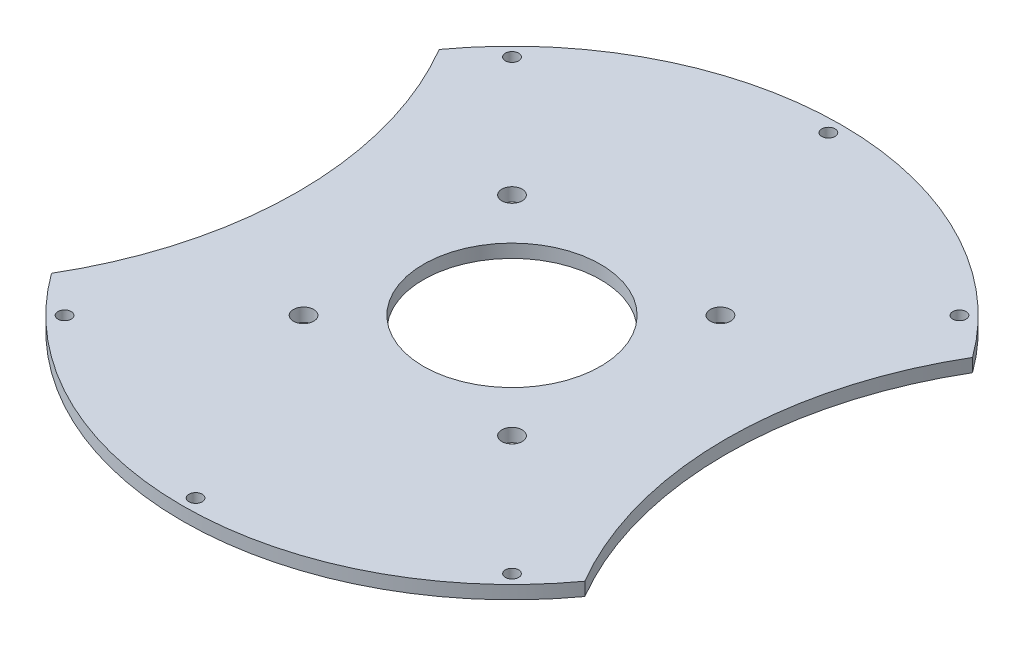
SolidWorks part; units mm, degrees
ref_plane "前视基准面" through (0, 0, 0) normal (0, 0, 1) x (1, 0, 0)
ref_plane "上视基准面" through (0, 0, 0) normal (0, 1, 0) x (1, 0, 0)
ref_plane "右视基准面" through (0, 0, 0) normal (1, 0, 0) x (0, 0, -1)
other "Configuration Table"
sketch "草图2" plane through (0, 0, 0) normal (0, 1, 0) x (1, 0, 0)
  line L1 (0, -103.5765) -> (0, 101.5106) construction
  line L2 (23.55, -23.55) -> (-23.55, -23.55)
  line L3 (23.55, -23.55) -> (23.55, 23.55)
  line L4 (23.55, 23.55) -> (-23.55, 23.55)
  line L5 (-23.55, -23.55) -> (-23.55, 23.55)
  line L6 (23.55, -23.55) -> (-23.55, 23.55) construction
  line L7 (23.55, 23.55) -> (-23.55, -23.55) construction
  arc A0 (60.2604, 43.8057) -> (-60.2604, 43.8057) centre (0, 0) ccw
  circle A2 centre (0, 71.5) radius 1.5
  circle A3 centre (50.5581, 50.5581) radius 1.5
  circle A5 centre (50.5581, -50.5581) radius 1.5
  circle A6 centre (0, -71.5) radius 1.5
  circle A7 centre (-50.5581, -50.5581) radius 1.5
  circle A9 centre (-50.5581, 50.5581) radius 1.5
  circle A12 centre (0, 0) radius 20
  arc A23 (-60.2604, -43.8057) -> (-60.2604, 43.8057) centre (-134.9405, 0) ccw
  arc A24 (60.2604, -43.8057) -> (60.2604, 43.8057) centre (134.9405, 0) cw
  circle A25 centre (71.5, 0) radius 1.5 [skipped]
  arc A26 (-60.2604, -43.8057) -> (60.2604, -43.8057) centre (0, 0) ccw
  circle A27 centre (-71.5, 0) radius 1.5 [skipped]
  circle A34 centre (-23.55, 23.55) radius 2.3
  circle A35 centre (23.55, 23.55) radius 2.3
  circle A36 centre (23.55, -23.55) radius 2.3
  circle A37 centre (-23.55, -23.55) radius 2.3
  point P22 (0, 0)
  dimension "D1" = 149
  dimension "D2" = 3
  dimension "D5" = 47.1
  dimension "D7" = 4.6
  dimension "D8" = 40
  dimension "D9" = 4.6
  dimension "D10" = 4.6
  dimension "D11" = 4.6
  dimension "D3" = 71.5
  dimension "D6" = 47.1
  dimension "D4" = 8
extrude "凸台-拉伸1" add sketch "草图2" along normal blind 3
